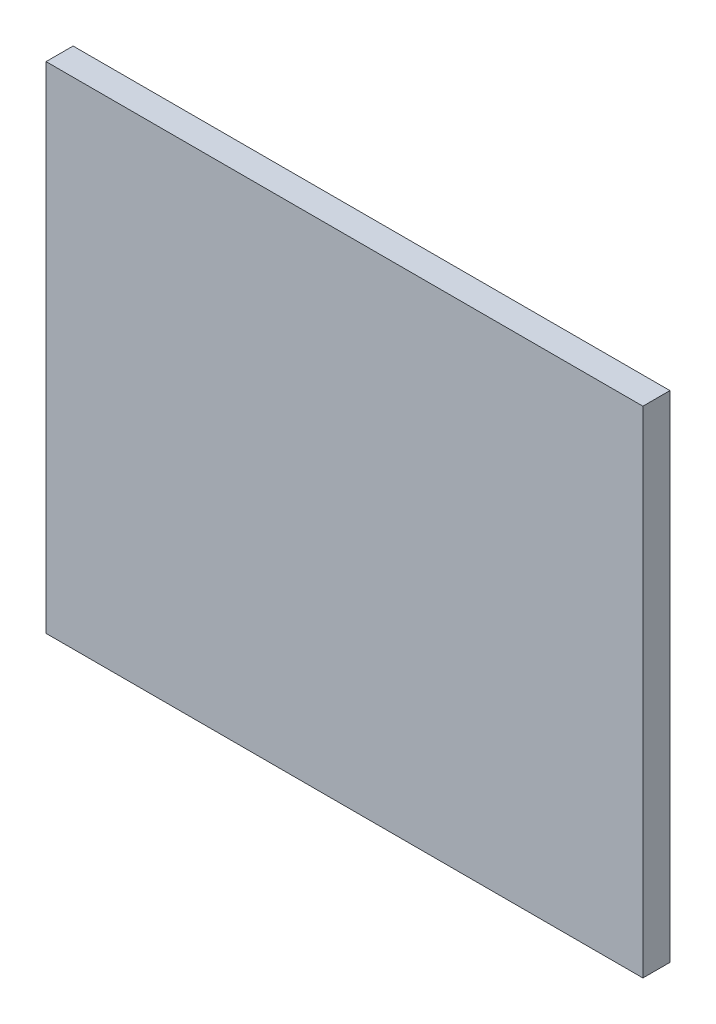
SolidWorks part; units mm, degrees
ref_plane "Front Plane" through (0, 0, 0) normal (0, 0, 1) x (1, 0, 0)
ref_plane "Top Plane" through (0, 0, 0) normal (0, 1, 0) x (1, 0, 0)
ref_plane "Right Plane" through (0, 0, 0) normal (1, 0, 0) x (0, 0, -1)
sketch "Sketch1" plane through (0, 0, 0) normal (0, 0, 1) x (1, 0, 0)
  line L1 (0, 0) -> (101.6, 0)
  line L2 (0, 0) -> (0, 84.3)
  line L3 (0, 84.3) -> (101.6, 84.3)
  line L4 (101.6, 0) -> (101.6, 84.3)
  line L5 (0, 0) -> (101.6, 84.3) construction
  line L6 (0, 84.3) -> (101.6, 0) construction
  point P4 (50.8, 42.15)
  dimension "D1" = 101.6
  dimension "D2" = 84.3
extrude "Boss-Extrude1" add sketch "Sketch1" along normal blind 4.6
ref_plane "Plane1" through (50.8, 0, 0) normal (-1, 0, 0) x (0, 0, 1)
equation "\"MDF\"= 4.8mm"
equation "\"Foamcore\"= 4.6mm"
equation "\"GMaterial\"= \"MDF\""
equation "\"PCB\" = 1.6mm"
equation "\"BaseWidth\" = 10in"
equation "\"SkidLength\" = 1in"
equation "\"SkidClearance\" = 0.4in"
equation "\"MotorMountLength\" = 2in"
equation "\"MotorMountWidth\" = \"GMaterial\""
equation "\"MotorMountHeight\" = 2.25in"
equation "\"UnoStackWidth\" = 77.4mm"
equation "\"UnoStackLength\" = 79.8mm"
equation "\"UnoStackHeight\" = 34.2mm"
equation "\"TallHexRiserHeight\" = 22.2mm"
equation "\"PingPongBallSize\" = 40mm"
equation "\"BarrelLength\" = 9in"
equation "\"BarrelSize\" = \"PingPongBallSize\""
equation "\"PlatformLength\" = 4in"
equation "\"PlatformWidth\" = 6in"
equation "\"WheelDiameter\"=2.99213"
equation "\"ServoMountHeight\"=2.49223"
equation "\"ServoGearHeight\" = 0.95330261in"
equation "\"ServoMountLength\"= 1.53774"
equation "\"PivotHoleRadius\"= 0.616358"
equation "\"PlatformMountHeight\" = 3.19"
equation "\"TensionOffSet\"= .3mm"
equation "\"MotorMountWedge\"=0.333333"
equation "\"LaserCutterOffset\"= .3mm"
equation "\"BumperWidth\"=11"
equation "\"PitcherWheelCompression\" = 2.5mm"
equation "\"PitchingWheelWidth\" = 26.2mm"
equation "\"PitchingWheelDiameter\" = 65.5mm"
equation "\"PitchingWheelMountOffset\" = 8.4mm"
equation "\"PitchingWheelInnerDiameter\" = 45.5mm"
equation "\"PitchingWheelBoltShoulder\" = 4.5mm"
equation "\"BrassCouplingLength\" = 18mm"
equation "\"PitchingMotorHeight\" = 57.0mm"
equation "\"PitchingMotorShaftTopHeight\" = \"PitchingMotorHeight\" - 44.1mm"
equation "\"PitchingMotorBodyHeight\" = 38mm"
equation "\"PitchingMotorTopShoulderHeight\" = 40.6mm - \"PitchingMotorBodyHeight\" "
equation "\"PitchingMotorBottomShoulderHeight\" = 40.2mm - \"PitchingMotorBodyHeight\""
equation "\"PitchingMotorBottomShaftHeight\" = \"PitchingMotorHeight\" - \"PitchingMotorShaftTopHeight\" - \"PitchingMotorTopShoulderHeight\" - \"PitchingMotorBodyHeight\" - \"PitchingMotorBottomShoulderHeight\""
equation "\"PitchingMotorShaftDiameter\" = 2.2mm"
equation "\"PitchingMotorBodyDiameter\" = 27.4mm"
equation "\"PitchingMotorTopShoulderDiameter\" = 9.8mm"
equation "\"PitchingMotorBottomShoulderDiameter\" = 9.8mm"
equation "\"BrassCouplingHexSize\" = 12mm"
equation "\"BrassCouplingBoreSize\" = 3.17mm"
equation "\"PitchingMotorMountingHoleDistance\" = 16mm"
equation "\"Acrylic\" = 4.4mm"
equation "\"PitchingMotorDistance\" = \"PitchingWheelDiameter\" + \"PingPongBallSize\" - \"PitcherWheelCompression\"*2"
equation "\"PitchingMotorPlatformOffset\"=1"
equation "\"ServoPlatformOffset\"=1.64173"
equation "\"BallBearingDiameter\" = 22mm"
equation "\"BallBearingWidth\" = 9mm"
equation "\"BallBearingHexShoulder\" = 9mm - 5.9mm"
equation "\"BallBearingHexSize\" = .36in"
equation "\"PlatformMountFootLength\"=0.857143"
equation "\"WheelWidth\"= 26mm"
equation "\"ServoMountReductionBackHeight\"=2.25"
equation "\"PlatformBottomWidthThird\" =  0.857143in"
equation "\"PlatformMountBackReductionHeight\"= 2.5in"
equation "\"PlatformMountBackReductionWidth\"= 3/7in"
equation "\"PlatformMountFrontReductionWidth\" =  1.46226in"
equation "\"PlatformMountFrontReductionHeight\" = 2.5in"
equation "\"HopperLongWallLength\" = 8.646in"
equation "\"HopperShortWallLength\" = 0.9571in"
equation "\"D1@Boss-Extrude1\"=\"Foamcore\""
equation "\"HopperHeight\" = 3.50in - \"Foamcore\""
equation "\"D2@Sketch1\"=\"HopperHeight\""
